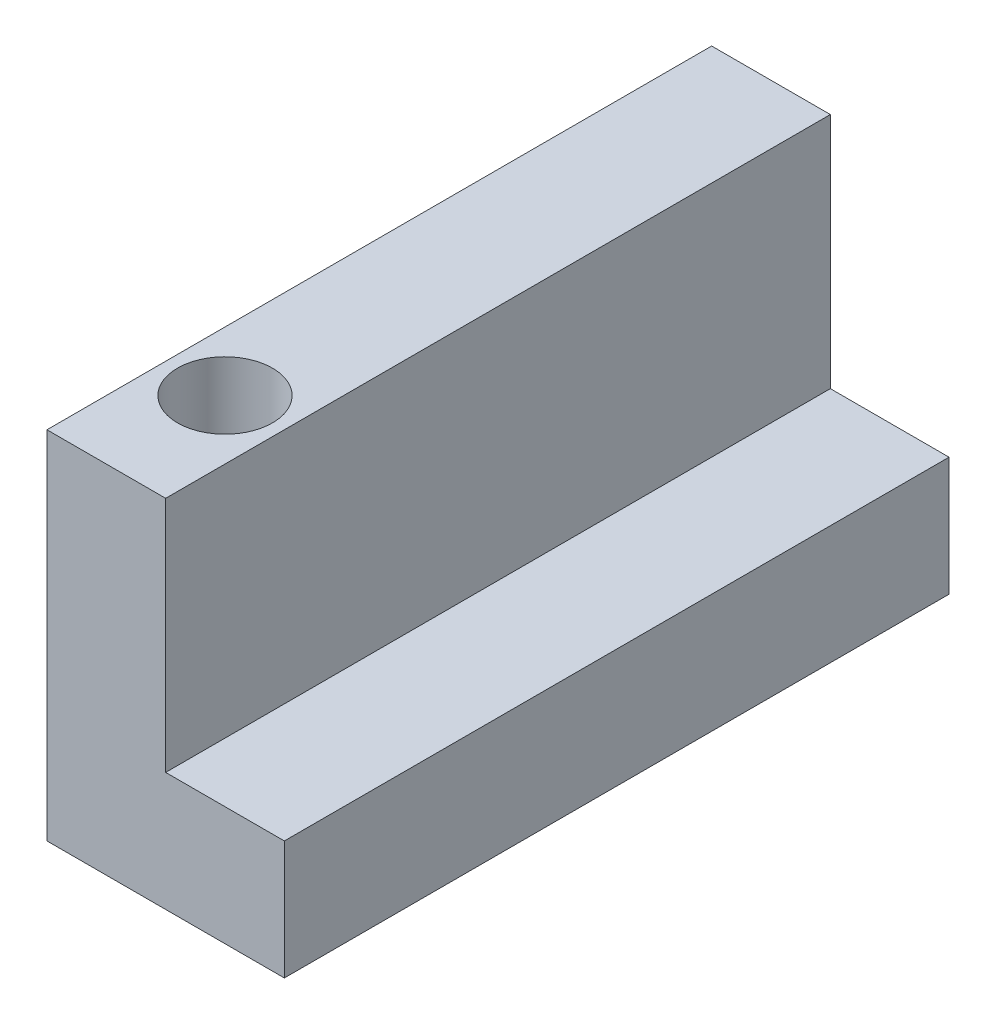
SolidWorks part; units mm, degrees
other "Markup1"
sketch "Sketch6" plane through (0, 0, 0) normal (0.7258, -0.6292, 0.2781) x (-0.261, -0.6259, -0.735)
ref_plane "Front Plane" through (0, 0, 0) normal (0, 0, 1) x (1, 0, 0)
ref_plane "Top Plane" through (0, 0, 0) normal (0, 1, 0) x (1, 0, 0)
ref_plane "Right Plane" through (0, 0, 0) normal (1, 0, 0) x (0, 0, -1)
sketch "Sketch1" plane through (0, 0, 0) normal (0, 0, 1) x (1, 0, 0)
  line L0 (0, 0) -> (-12.7, 0)
  line L1 (-12.7, 0) -> (-12.7, 19.05)
  line L2 (-12.7, 19.05) -> (-6.35, 19.05)
  line L3 (-6.35, 19.05) -> (-6.35, 6.35)
  line L4 (-6.35, 6.35) -> (0, 6.35)
  line L5 (0, 6.35) -> (0, 0)
  dimension "D1" = 6.35
  dimension "D2" = 6.35
  dimension "D3" = 6.35
  dimension "D4" = 12.7
extrude "Boss-Extrude1" add sketch "Sketch1" against normal blind 381
sketch "Sketch2" plane through (-12.7, 0, 0) normal (-1, 0, 0) x (0, 0, 1)
  line L0 (-381, 0) -> (0, 0) construction
  line L2 (0, 19.05) -> (0, 0) construction
  circle A0 centre (-365.76, 12.065) radius 3.175
  dimension "D1" = 6.35
  dimension "D2" = 12.065
  dimension "D3" = 365.76
extrude "Cut-Extrude1" cut sketch "Sketch2" against normal up to next
sketch "Sketch3" plane through (0, 19.05, 0) normal (0, 1, 0) x (1, 0, 0)
  line L0 (-9.525, 381) -> (-9.525, 0) construction
  line L1 (-6.35, 381) -> (-12.7, 381) construction
  line L2 (-6.35, 0) -> (-12.7, 0) construction
  circle A0 centre (-9.525, 6.35) radius 2.54
  circle A1 centre (-9.525, 374.65) radius 2.54
  dimension "D1" = 5.08
  dimension "D3" = 6.35
  dimension "D2" = 6.35
extrude "Cut-Extrude2" cut sketch "Sketch3" against normal blind 7.62
sketch "Sketch4" plane through (0, 0, 0) normal (0, -1, 0) x (1, 0, 0)
  line L0 (-9.525, 0) -> (-9.525, -381) construction
  line L1 (-12.7, 0) -> (0, 0) construction
  line L2 (-12.7, -381) -> (0, -381) construction
  line L3 (0, -381) -> (0, 0) construction
  circle A0 centre (-9.525, -374.65) radius 2.54
  circle A1 centre (-9.525, -6.35) radius 2.54
  dimension "D2" = 5.08
  dimension "D1" = 9.525
  dimension "D3" = 6.35
  dimension "D4" = 6.35
extrude "Cut-Extrude3" cut sketch "Sketch4" against normal blind 7.62
sketch "Sketch5" plane through (0, 0, -381) normal (0, 0, -1) x (-1, 0, 0)
  line L1 (6.35, 6.35) -> (0, 6.35)
  line L2 (6.35, 6.35) -> (6.35, 0)
  line L3 (6.35, 0) -> (0, 0)
  line L4 (0, 6.35) -> (0, 0)
extrude "Cut-Extrude4" cut sketch "Sketch5" against normal blind 345.44
sketch "Sketch7" plane through (-6.35, 0, 0) normal (1, 0, 0) x (0, 0, -1)
  line L0 (35.56, 0) -> (381, 0) construction
  line L1 (35.56, 0) -> (381, 0)
  line L2 (35.56, 0) -> (35.56, 19.05)
  line L3 (35.56, 19.05) -> (381, 19.05)
  line L4 (381, 0) -> (381, 19.05)
extrude "Cut-Extrude5" cut sketch "Sketch7" against normal through all
